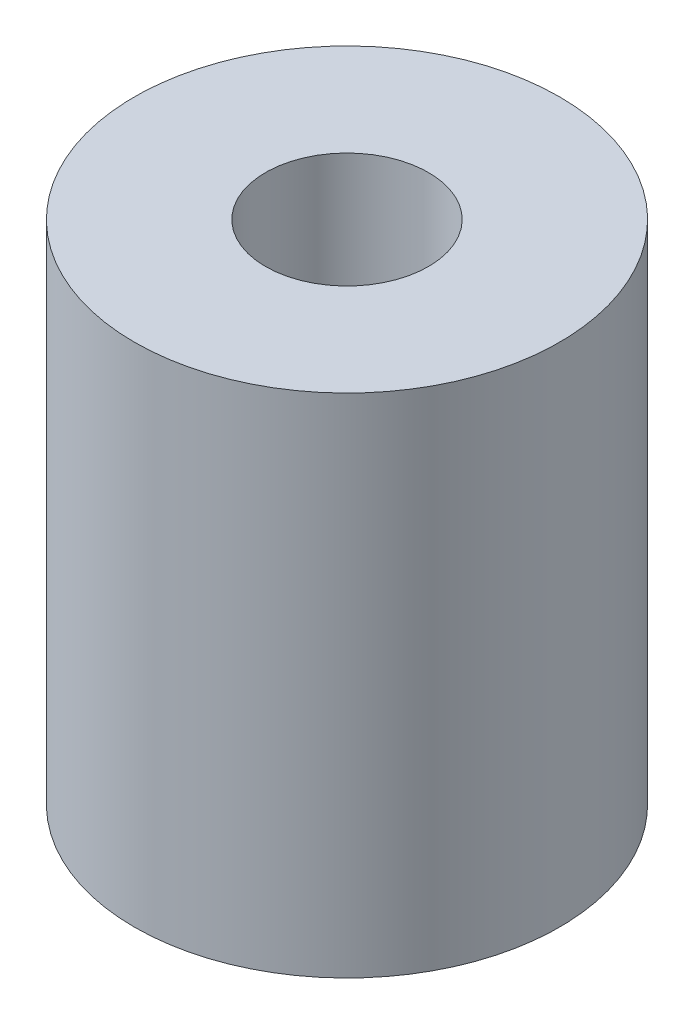
SolidWorks part; units mm, degrees
ref_plane "Płaszczyzna przednia" through (0, 0, 0) normal (0, 0, 1) x (1, 0, 0)
ref_plane "Płaszczyzna górna" through (0, 0, 0) normal (0, 1, 0) x (1, 0, 0)
ref_plane "Płaszczyzna prawa" through (0, 0, 0) normal (1, 0, 0) x (0, 0, -1)
sketch "Sketch1" plane through (0, 0, 0) normal (0, 1, 0) x (1, 0, 0)
  circle A0 centre (0, 0) radius 6
  circle A1 centre (0, 0) radius 2.3
  dimension "D1" = 12
  dimension "D2" = 4.6
extrude "Boss-Extrude1" add sketch "Sketch1" along normal blind 14.3
